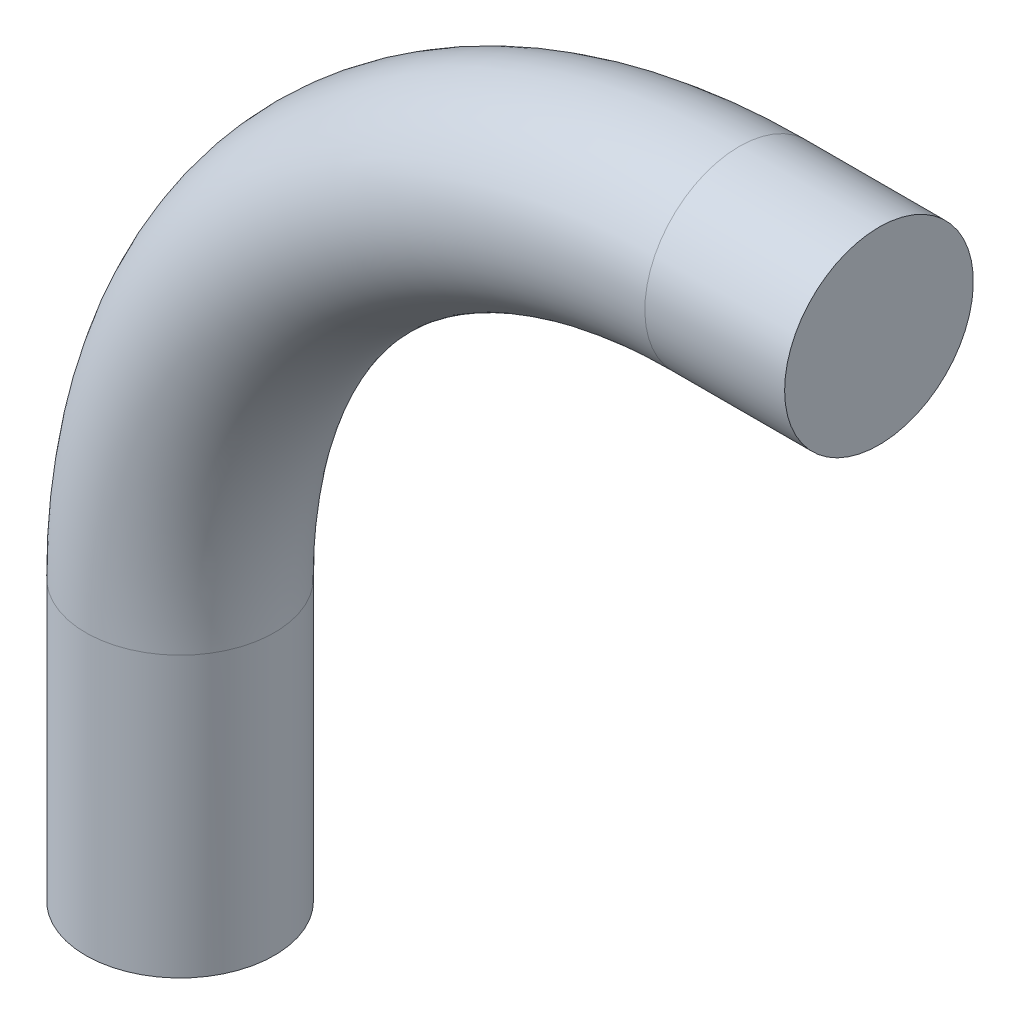
SolidWorks part; units mm, degrees
ref_plane "Front Plane" through (0, 0, 0) normal (0, 0, 1) x (1, 0, 0)
ref_plane "Top Plane" through (0, 0, 0) normal (0, 1, 0) x (1, 0, 0)
ref_plane "Right Plane" through (0, 0, 0) normal (1, 0, 0) x (0, 0, -1)
sketch "Sketch1" plane through (0, 0, 0) normal (0, 0, 1) x (1, 0, 0)
  line L0 (0, 0) -> (0, 20)
  line L1 (40, 60) -> (50, 60)
  arc A0 (0, 20) -> (40, 60) centre (40, 20) cw
  point P6 (0, 60)
  dimension "D3" = 40
  dimension "D1" = 50
  dimension "D2" = 60
  dimension "D4" = 90
sketch "Sketch2" plane through (0, 0, 0) normal (0, 1, 0) x (1, 0, 0)
  circle A0 centre (0, 0) radius 6.75
  dimension "D1" = 13.5
sweep "Sweep1" add profiles "Sketch2" path "Sketch1"
